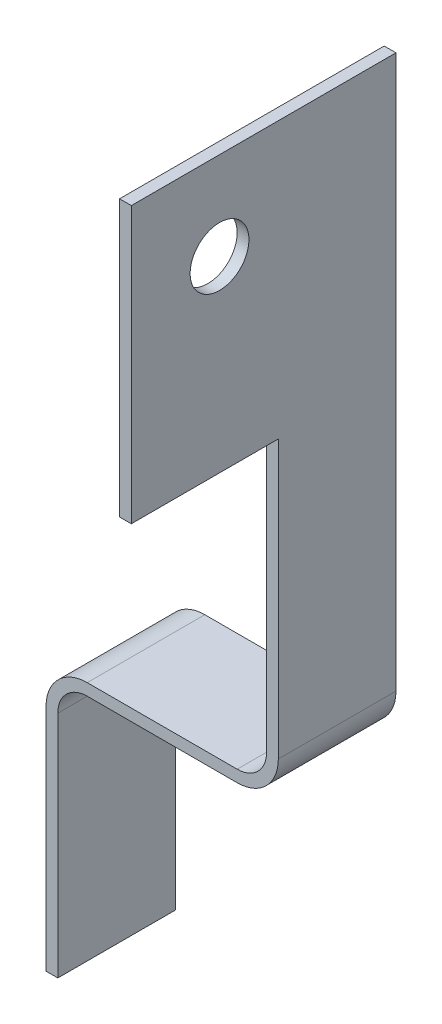
SolidWorks part; units mm, degrees
ref_plane "Front Plane" through (0, 0, 0) normal (0, 0, 1) x (1, 0, 0)
ref_plane "Top Plane" through (0, 0, 0) normal (0, 1, 0) x (1, 0, 0)
ref_plane "Right Plane" through (0, 0, 0) normal (1, 0, 0) x (0, 0, -1)
ref_plane "Plane1" through (0, 0, 293.0295) normal (0, 0, -1) x (-1, 0, 0)
sketch "Sketch1" plane through (0, 0, 293.0295) normal (0, 0, -1) x (-1, 0, 0)
  line L0 (-159.6, 15.6281) -> (-159.6, 73.6281)
  line L1 (-159.6, 73.6281) -> (-175.4, 73.6281)
  line L2 (-175.4, 73.6281) -> (-175.4, 15.6281)
  line L3 (-175.4, 15.6281) -> (-159.6, 15.6281)
extrude "Boss-Extrude1" add sketch "Sketch1" against normal blind 8
sketch "Sketch2" plane through (0, 0, 293.0295) normal (0, 0, -1) x (-1, 0, 0)
  line L0 (-174.6, 73.6281) -> (-174.6, 34.0281)
  line L1 (-174.6, 34.0281) -> (-159.6, 34.0281)
  line L2 (-159.6, 34.0281) -> (-159.6, 73.6281)
  line L3 (-159.6, 73.6281) -> (-174.6, 73.6281)
extrude "Cut-Extrude1" cut sketch "Sketch2" against normal through all
sketch "Sketch3" plane through (0, 0, 301.0295) normal (0, 0, 1) x (1, 0, 0)
  line L0 (174.6, 54.8829) -> (174.6, 73.6281)
  line L1 (174.6, 73.6281) -> (175.4, 73.6281)
  line L2 (175.4, 73.6281) -> (175.4, 54.8829)
  line L3 (175.4, 54.8829) -> (174.6, 54.8829)
extrude "Boss-Extrude2" add sketch "Sketch3" along normal blind 10
sketch "Sketch4" plane through (0, 0, 301.0295) normal (0, 0, 1) x (1, 0, 0)
  line L0 (175.4, 33.2281) -> (160.4, 33.2281)
  line L1 (160.4, 33.2281) -> (160.4, 15.6281)
  line L2 (160.4, 15.6281) -> (175.4, 15.6281)
  line L3 (175.4, 15.6281) -> (175.4, 33.2281)
extrude "Cut-Extrude2" cut sketch "Sketch4" against normal through all
hole_wizard "Hole1" positions "Sketch6" profile "Sketch5" legacy
sketch "Sketch6" plane through (174.6, 0, 0) normal (-1, 0, 0) x (0, 0, 1)
  point P0 (305.0295, 67.6281)
sketch "Sketch5" plane through (174.6, 67.6281, 305.0295) normal (0, 1, 0) x (0, 0, 1)
  line L0 (0, 0) -> (0, 0.8001)
  line L1 (0, 0.8001) -> (2, 0.8001)
  line L2 (2, 0.8001) -> (2, 0)
  line L3 (2, 0) -> (0, 0)
  line L4 (0, 110) -> (0, -10) construction
  dimension "Diameter" = 4
  dimension "Depth" = 0.8001
fillet "Fillet1" radius 2 1 edges at (160.4, 33.2281, 297.0295)
fillet "Fillet2" radius 2 1 edges at (174.6, 34.0281, 297.0295)
fillet "Fillet3" radius 2.8 1 edges at (159.6, 34.0281, 297.0295)
fillet "Fillet4" radius 2.8 1 edges at (175.4, 33.2281, 297.0295)
